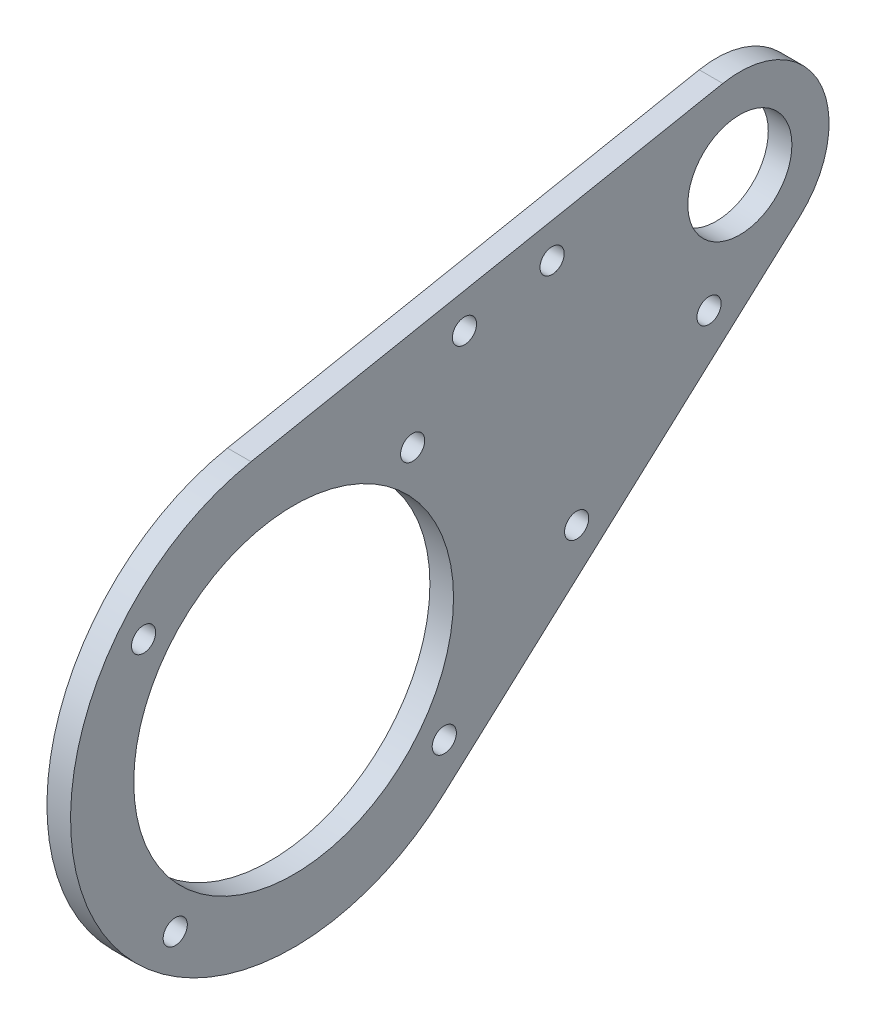
SolidWorks part; units mm, degrees
ref_plane "Front Plane" through (0, 0, 0) normal (0, 0, 1) x (1, 0, 0)
ref_plane "Top Plane" through (0, 0, 0) normal (0, 1, 0) x (1, 0, 0)
ref_plane "Right Plane" through (0, 0, 0) normal (1, 0, 0) x (0, 0, -1)
sketch "Sketch1" plane through (0, 0, 0) normal (1, 0, 0) x (0, 0, -1)
  line L0 (-5.7244, 29.4488) -> (57.7102, 41.7795)
  line L1 (0, 0) -> (60, 30) construction
  line L3 (20.1244, -22.2488) -> (68.0498, 21.1005)
  circle A0 centre (0, 0) radius 21.5
  circle A1 centre (60, 30) radius 7
  arc A2 (-5.7244, 29.4488) -> (20.1244, -22.2488) centre (0, 0) ccw
  arc A3 (68.0498, 21.1005) -> (57.7102, 41.7795) centre (60, 30) ccw
  dimension "D1" = 43
  dimension "D2" = 60
  dimension "D4" = 14
  dimension "D3" = 24
  dimension "D5" = 60
  dimension "D6" = 30
extrude "Boss-Extrude1" add sketch "Sketch1" along normal blind 3.175
sketch "Sketch2" plane through (3.175, 0, 0) normal (1, 0, 0) x (0, 0, -1)
  line L0 (20.2591, -15.9247) -> (60.6527, 20.6121) construction
  line L2 (20.1244, -22.2488) -> (68.0498, 21.1005) construction
  line L3 (0, 0) -> (60, 30) construction
  line L4 (-0.5843, 25.7621) -> (52.8813, 36.155) construction
  circle A0 centre (0, 0) radius 25.75 construction
  circle A1 centre (-20.1758, 16) radius 1.625
  circle A2 centre (16.004, 20.2551) radius 1.625
  circle A3 centre (20.2591, -15.9247) radius 1.625
  circle A4 centre (-15.9207, -20.1798) radius 1.625
  circle A5 centre (38.0581, 0.1749) radius 1.625
  circle A6 centre (55.8571, 16.2744) radius 1.625
  circle A8 centre (22.9747, 30.3416) radius 1.625
  circle A9 centre (34.7543, 32.6313) radius 1.625
  point P13 (0.0416, 0.0377)
  dimension "D1" = 51.5
  dimension "D2" = 3.25
  dimension "D6" = 3.25
  dimension "D7" = 3.25
  dimension "D10" = 3.25
  dimension "D3" = 16
  dimension "D5" = 4.5998
  dimension "D8" = 24
  dimension "D9" = 24
  dimension "D11" = 12
  dimension "D4" = 4
extrude "Cut-Extrude1" cut sketch "Sketch2" against normal through all
